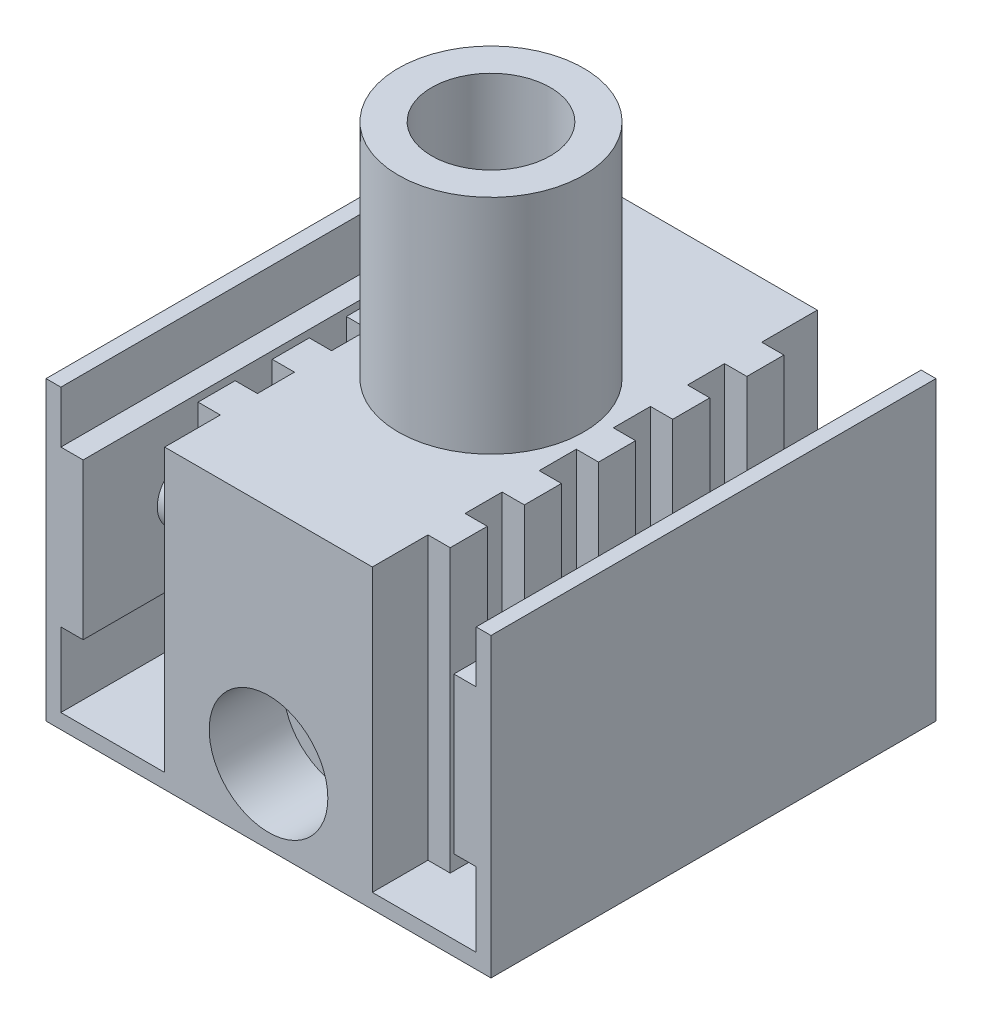
SolidWorks part; units mm, degrees
ref_plane "Plano frontal" through (0, 0, 0) normal (0, 0, 1) x (1, 0, 0)
ref_plane "Plano superior" through (0, 0, 0) normal (0, 1, 0) x (1, 0, 0)
ref_plane "Plano direito" through (0, 0, 0) normal (1, 0, 0) x (0, 0, -1)
sketch "Esboço1" plane through (0, 0, 0) normal (0, 1, 0) x (1, 0, 0)
  circle A0 centre (0, 0) radius 12.5
  dimension "D1" = 25
extrude "Ressalto-extrusão1" add sketch "Esboço1" along normal blind 30
sketch "Esboço2" plane through (0, 30, 0) normal (0, 1, 0) x (1, 0, 0)
  circle A0 centre (0, 0) radius 8
extrude "Corte-extrusão1" cut sketch "Esboço2" against normal blind 15
sketch "Esboço3" plane through (0, 0, 0) normal (0, -1, 0) x (1, 0, 0)
  line L1 (-1.5, 2.5) -> (1.5, 2.5)
  line L2 (-1.5, 2.5) -> (-1.5, -2.5)
  line L3 (-1.5, -2.5) -> (1.5, -2.5)
  line L4 (1.5, 2.5) -> (1.5, -2.5)
  circle A0 centre (0, 0) radius 12.5 construction
  dimension "D1" = 3
  dimension "D2" = 5
  dimension "D3" = 1.5
  dimension "D4" = 2.5
extrude "Corte-extrusão2" cut sketch "Esboço3" against normal blind 6.5
sketch "Esboço4" plane through (0, 0, 0) normal (0, -1, 0) x (1, 0, 0)
  line L1 (-30, -30) -> (30, -30)
  line L2 (-30, -30) -> (-30, 30)
  line L3 (-30, 30) -> (30, 30)
  line L4 (30, -30) -> (30, 30)
  line L5 (-30, -30) -> (30, 30) construction
  line L6 (-30, 30) -> (30, -30) construction
  point P0 (0, 0)
  dimension "D1" = 60
  dimension "D2" = 60
extrude "Ressalto-extrusão2" add sketch "Esboço4" along normal blind 40
sketch "Esboço5" plane through (0, 0, 0) normal (0, 1, 0) x (1, 0, 0)
  line L0 (30, -30) -> (-30, -30) construction
  line L1 (-28, 30) -> (-17, 30)
  line L2 (-28, 30) -> (-28, -30)
  line L3 (-28, -30) -> (-17, -30)
  line L4 (-17, 30) -> (-17, -30)
  line L5 (17, 30) -> (28, 30)
  line L6 (17, 30) -> (17, -30)
  line L7 (17, -30) -> (28, -30)
  line L8 (28, 30) -> (28, -30)
  line L9 (-30, -30) -> (-30, 30) construction
  line L10 (30, 30) -> (30, -30) construction
  dimension "D1" = 11
  dimension "D2" = 11
  dimension "D3" = 60
  dimension "D4" = 60
  dimension "D5" = 0
  dimension "D6" = 0
  dimension "D7" = 2
  dimension "D8" = 2
extrude "Corte-extrusão3" cut sketch "Esboço5" against normal blind 35
sketch "Esboço6" plane through (0, 0, 0) normal (0, 1, 0) x (1, 0, 0)
  line L1 (-28, 30) -> (-17, 30)
  line L2 (-28, 30) -> (-28, -30)
  line L3 (-28, -30) -> (-17, -30)
  line L4 (-17, 30) -> (-17, -30)
  line L5 (17, 30) -> (28, 30)
  line L6 (17, 30) -> (17, -30)
  line L7 (17, -30) -> (28, -30)
  line L8 (28, 30) -> (28, -30)
extrude "Corte-extrusão4" cut sketch "Esboço6" against normal blind 38
sketch "Esboço7" plane through (-28, 0, 0) normal (1, 0, 0) x (0, 0, -1)
  line L0 (30, 0) -> (-30, 0) construction
  line L1 (-30, -7) -> (30, -7)
  line L2 (-30, -7) -> (-30, -28)
  line L3 (-30, -28) -> (30, -28)
  line L4 (30, -7) -> (30, -28)
  line L7 (-30, -38) -> (-30, 0) construction
  line L8 (30, -38) -> (30, 0) construction
  dimension "D1" = 21
  dimension "D2" = 7
  dimension "D3" = 0
  dimension "D4" = 0
extrude "Ressalto-extrusão3" add sketch "Esboço7" along normal blind 3
sketch "Esboço8" plane through (28, 0, 0) normal (-1, 0, 0) x (0, 0, 1)
  line L0 (-30, -40) -> (-30, 0) construction
  line L1 (-30, -7) -> (30, -7)
  line L2 (-30, -7) -> (-30, -28)
  line L3 (-30, -28) -> (30, -28)
  line L4 (30, -7) -> (30, -28)
  line L5 (30, -40) -> (30, 0) construction
  line L6 (30, 0) -> (-30, 0) construction
  dimension "D1" = 7
  dimension "D2" = 21
extrude "Ressalto-extrusão4" add sketch "Esboço8" along normal blind 3.0045
sketch "Esboço9" plane through (24.9955, 0, 0) normal (-1, 0, 0) x (0, 0, 1)
  line L1 (-16, -13.5) -> (16, -13.5)
  line L3 (-16, -21.5) -> (16, -21.5)
  line L5 (30, -7) -> (-30, -7) construction
  arc A0 (-16, -13.5) -> (-16, -21.5) centre (-16, -17.5) ccw
  arc A1 (16, -21.5) -> (16, -13.5) centre (16, -17.5) ccw
  dimension "D2" = 6.5
extrude "Ressalto-extrusão5" add sketch "Esboço9" along normal blind 2.9952
sketch "Esboço14" plane through (-25, 0, 0) normal (1, 0, 0) x (0, 0, -1)
  line L1 (-16, -13.5) -> (16, -13.5)
  line L3 (-16, -21.5) -> (16, -21.5)
  line L6 (-30, -28) -> (30, -28) construction
  arc A0 (-16, -13.5) -> (-16, -21.5) centre (-16, -17.5) ccw
  arc A1 (16, -21.5) -> (16, -13.5) centre (16, -17.5) ccw
  dimension "D4" = 6.5
extrude "Ressalto-extrusão6" add sketch "Esboço14" along normal blind 3
sketch "Esboço15" plane through (0, 15, 0) normal (0, 1, 0) x (1, 0, 0)
  circle A0 centre (0, 0) radius 8
extrude "Corte-extrusão5" cut sketch "Esboço15" against normal through all
sketch "Esboço19" plane through (-17, 0, 0) normal (-1, 0, 0) x (0, 0, 1)
  line L0 (-17.5, 0) -> (-12.5, 0)
  line L1 (-30, 0) -> (-22.5, 0)
  line L2 (-30, 0) -> (-30, -38)
  line L3 (-30, -38) -> (-22.5, -38)
  line L4 (-22.5, 0) -> (-22.5, -38)
  line L5 (-17.5, 0) -> (-17.5, -38)
  line L6 (-17.5, -38) -> (-12.5, -38)
  line L7 (-12.5, 0) -> (-12.5, -38)
  line L8 (30, 0) -> (-30, 0) construction
  line L10 (-7.5, 0) -> (-2.5, 0)
  line L11 (-7.5, 0) -> (-7.5, -38)
  line L12 (-7.5, -38) -> (-2.5, -38)
  line L13 (-2.5, 0) -> (-2.5, -38)
  line L14 (2.5, 0) -> (7.5, 0)
  line L15 (2.5, 0) -> (2.5, -38)
  line L16 (2.5, -38) -> (7.5, -38)
  line L17 (7.5, 0) -> (7.5, -38)
  line L18 (12.5, 0) -> (17.5, 0)
  line L19 (12.5, 0) -> (12.5, -38)
  line L20 (12.5, -38) -> (17.5, -38)
  line L21 (17.5, 0) -> (17.5, -38)
  line L22 (22.5, 0) -> (30, 0)
  line L23 (22.5, 0) -> (22.5, -38)
  line L24 (22.5, -38) -> (30, -38)
  line L25 (30, 0) -> (30, -38)
  dimension "D1" = 7.5
  dimension "D2" = 38
  dimension "D3" = 5
  dimension "D4" = 5
  dimension "D5" = 0
  dimension "D6" = 5
  dimension "D7" = 5
  dimension "D8" = 5
  dimension "D9" = 5
  dimension "D10" = 5
  dimension "D11" = 5
  dimension "D12" = 5
  dimension "D13" = 7.5
extrude "Corte-extrusão7" cut sketch "Esboço19" against normal blind 3
sketch "Esboço20" plane through (17, 0, 0) normal (1, 0, 0) x (0, 0, -1)
  line L0 (30, 0) -> (-30, 0) construction
  line L1 (-30, 0) -> (-22.5, 0)
  line L2 (-30, 0) -> (-30, -38)
  line L3 (-30, -38) -> (-22.5, -38)
  line L4 (-22.5, 0) -> (-22.5, -38)
  line L5 (-17.5, 0) -> (-12.5, 0)
  line L6 (-17.5, 0) -> (-17.5, -38)
  line L7 (-17.5, -38) -> (-12.5, -38)
  line L8 (-12.5, 0) -> (-12.5, -38)
  line L10 (-7.5, 0) -> (-2.5, 0)
  line L11 (-7.5, 0) -> (-7.5, -38)
  line L12 (-7.5, -38) -> (-2.5, -38)
  line L13 (-2.5, 0) -> (-2.5, -38)
  line L14 (2.5, 0) -> (7.5, 0)
  line L15 (2.5, 0) -> (2.5, -38)
  line L16 (2.5, -38) -> (7.5, -38)
  line L17 (7.5, 0) -> (7.5, -38)
  line L18 (12.5, 0) -> (17.5, 0)
  line L19 (12.5, 0) -> (12.5, -38)
  line L20 (12.5, -38) -> (17.5, -38)
  line L21 (17.5, 0) -> (17.5, -38)
  line L22 (22.5, 0) -> (30, 0)
  line L23 (22.5, 0) -> (22.5, -38)
  line L24 (22.5, -38) -> (30, -38)
  line L25 (30, 0) -> (30, -38)
  dimension "D1" = 38
  dimension "D2" = 7.5
  dimension "D3" = 5
  dimension "D4" = 5
  dimension "D5" = 5
  dimension "D6" = 5
  dimension "D7" = 5
  dimension "D8" = 5
  dimension "D9" = 5
  dimension "D10" = 5
  dimension "D11" = 5
  dimension "D12" = 7.5
extrude "Corte-extrusão8" cut sketch "Esboço20" against normal blind 3
sketch "Esboço21" plane through (0, 0, 30) normal (0, 0, 1) x (1, 0, 0)
  line L0 (30, -40) -> (-30, -40) construction
  circle A0 centre (0, -30) radius 8
  point P4 (0, -40)
  dimension "D1" = 10
extrude "Corte-extrusão9" cut sketch "Esboço21" against normal blind 10
sketch "Esboço22" plane through (0, 0, -30) normal (0, 0, -1) x (-1, 0, 0)
  line L0 (30, -40) -> (-30, -40) construction
  circle A0 centre (0, -30) radius 8
  dimension "D1" = 10
extrude "Corte-extrusão10" cut sketch "Esboço22" against normal blind 10
sketch "Esboço24" plane through (0, 0, -20) normal (0, 0, -1) x (-1, 0, 0)
  circle A0 centre (0, -30) radius 5
extrude "Corte-extrusão11" cut sketch "Esboço24" against normal through all
